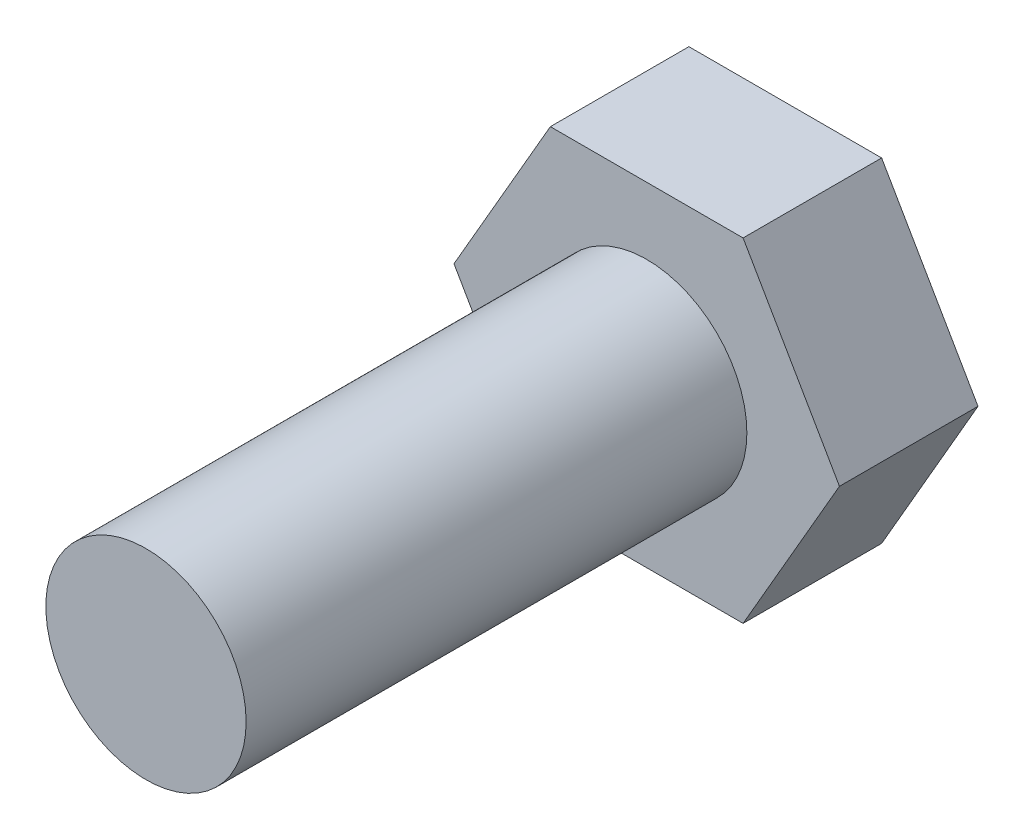
SolidWorks part; units mm, degrees
material "AISI 304"
ref_plane "Płaszczyzna przednia" through (0, 0, 0) normal (0, 0, 1) x (1, 0, 0)
ref_plane "Płaszczyzna górna" through (0, 0, 0) normal (0, 1, 0) x (1, 0, 0)
ref_plane "Płaszczyzna prawa" through (0, 0, 0) normal (1, 0, 0) x (0, 0, -1)
sketch "Sketch1" plane through (0, 0, 0) normal (0, 0, 1) x (1, 0, 0)
  line L1 (-2.8868, 5) -> (-5.7735, 0)
  line L2 (-5.7735, 0) -> (-2.8868, -5)
  line L3 (-2.8868, -5) -> (2.8868, -5)
  line L4 (2.8868, -5) -> (5.7735, 0)
  line L5 (5.7735, 0) -> (2.8868, 5)
  line L6 (2.8868, 5) -> (-2.8868, 5)
  circle A0 centre (0, 0) radius 5 construction
  dimension "D1" = 10
extrude "Boss-Extrude1" add sketch "Sketch1" along normal blind 4.15
sketch "Sketch2" plane through (0, 0, 4.15) normal (0, 0, 1) x (1, 0, 0)
  circle A0 centre (0, 0) radius 3
  dimension "D1" = 6
extrude "Boss-Extrude2" add sketch "Sketch2" along normal blind 15
